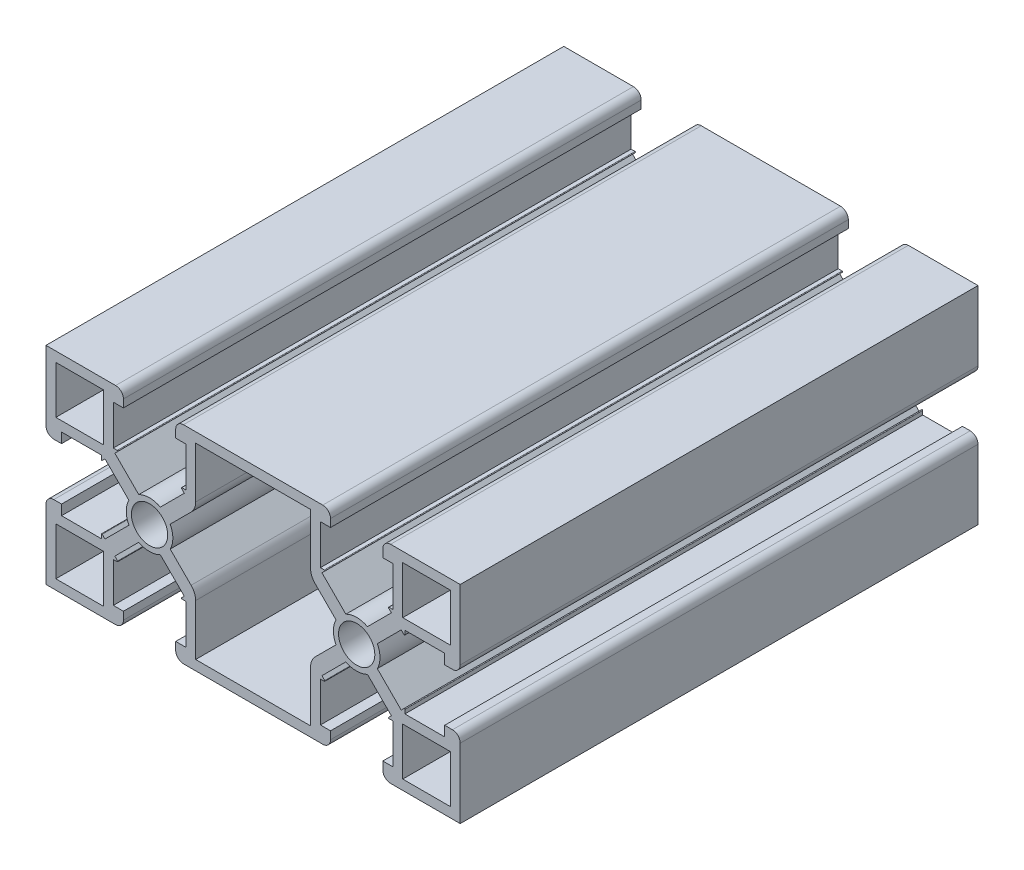
SolidWorks part; units mm, degrees
ref_plane "前视基准面" through (0, 0, 0) normal (0, 0, 1) x (1, 0, 0)
ref_plane "上视基准面" through (0, 0, 0) normal (0, 1, 0) x (1, 0, 0)
ref_plane "右视基准面" through (0, 0, 0) normal (1, 0, 0) x (0, 0, -1)
sketch "草图1" plane through (0, 0, 0) normal (0, 0, 1) x (1, 0, 0)
  line L0 (-40, 20) -> (-40, -20) construction
  line L1 (-27, 17) -> (-27, 9.3142)
  line L2 (-40, 20) -> (-40, 6.55)
  line L3 (-40, -20) -> (0, -20) construction
  line L4 (-40, 20) -> (-20, 0) construction
  line L5 (0, -20) -> (0, 20) construction
  line L6 (-28.9, 8.9) -> (-38.1, 8.9)
  line L7 (0, 0) -> (-40, 0) construction
  line L8 (-28.9, 8.9) -> (-28.9, 18.1)
  line L9 (-28.9, 18.1) -> (-38.1, 18.1)
  line L10 (-38.1, 8.9) -> (-38.1, 18.1)
  line L11 (-28.9, 8.9) -> (-38.1, 18.1) construction
  line L12 (-28.9, 18.1) -> (-38.1, 8.9) construction
  line L13 (-40, 20) -> (0, 20) construction
  line L14 (-38.5, 5.05) -> (-37, 5.05)
  line L15 (-25.05, 17) -> (-27, 17)
  line L16 (-25.05, 18.5) -> (-25.05, 17)
  line L17 (-40, 20) -> (-26.55, 20)
  line L18 (-26.7071, 8.6071) -> (-22.0869, 3.9869)
  line L19 (-37, 5.05) -> (-37, 7)
  line L20 (-37, 7) -> (-29.3142, 7)
  line L21 (-28.6071, 6.7071) -> (-23.9869, 2.0869)
  line L22 (-29.3142, 7) -> (-29.3142, 6.2414)
  line L23 (-29.1435, 6.1707) -> (-28.6071, 6.7071)
  line L24 (-29.3142, 7) -> (-28.9, 7) construction
  line L25 (-28.9, 7) -> (-28.6071, 6.7071) construction
  line L26 (-37, 7) -> (-37, 8.9) construction
  line L27 (-38.1, 8.9) -> (-40, 8.9) construction
  line L28 (-26.1707, 9.1435) -> (-26.7071, 8.6071)
  line L29 (-27, 9.3142) -> (-26.2414, 9.3142)
  line L30 (-20, 0) -> (-20, 20) construction
  line L31 (-13.2929, 8.6071) -> (-17.9131, 3.9869)
  line L32 (-13, 9.3142) -> (-13.7586, 9.3142)
  line L33 (-13.8293, 9.1435) -> (-13.2929, 8.6071)
  line L34 (-14.95, 18.5) -> (-14.95, 17)
  line L35 (-14.95, 17) -> (-13, 17)
  line L36 (-13, 17) -> (-13, 9.3142)
  line L37 (13.45, 20) -> (-13.45, 20)
  line L38 (13.45, -20) -> (-13.45, -20)
  line L39 (-11.9787, 6.1213) -> (-16.0131, 2.0869)
  line L40 (-11.1, 18.1) -> (-11.1, 8.2426)
  line L41 (-28.6071, 6.7071) -> (-26.7071, 8.6071) construction
  line L42 (-14.95, -18.5) -> (-14.95, -17)
  line L43 (-14.95, -17) -> (-13, -17)
  line L44 (-13, -17) -> (-13, -9.3142)
  line L45 (-13.8293, -9.1435) -> (-13.2929, -8.6071)
  line L46 (-13, -9.3142) -> (-13.7586, -9.3142)
  line L47 (-11.1, -18.1) -> (-11.1, -8.2426)
  line L48 (-11.9787, -6.1213) -> (-16.0131, -2.0869)
  line L49 (-13.2929, -8.6071) -> (-17.9131, -3.9869)
  line L50 (-26.7071, -8.6071) -> (-22.0869, -3.9869)
  line L51 (-28.6071, -6.7071) -> (-23.9869, -2.0869)
  line L52 (-29.3142, -7) -> (-29.3142, -6.2414)
  line L53 (-29.1435, -6.1707) -> (-28.6071, -6.7071)
  line L54 (-26.1707, -9.1435) -> (-26.7071, -8.6071)
  line L55 (-27, -9.3142) -> (-26.2414, -9.3142)
  line L56 (-27, -17) -> (-27, -9.3142)
  line L57 (-37, -7) -> (-29.3142, -7)
  line L58 (-37, -5.05) -> (-37, -7)
  line L59 (-38.5, -5.05) -> (-37, -5.05)
  line L60 (-40, -20) -> (-40, -6.55)
  line L61 (-38.1, -8.9) -> (-38.1, -18.1)
  line L62 (-28.9, -8.9) -> (-38.1, -8.9)
  line L63 (-28.9, -8.9) -> (-28.9, -18.1)
  line L64 (-28.9, -18.1) -> (-38.1, -18.1)
  line L65 (-25.05, -17) -> (-27, -17)
  line L66 (-25.05, -18.5) -> (-25.05, -17)
  line L67 (-40, -20) -> (-26.55, -20)
  line L68 (-11.1, 18.1) -> (11.1, 18.1)
  line L69 (-11.1, -18.1) -> (11.1, -18.1)
  line L70 (14.95, -18.5) -> (14.95, -17)
  line L71 (14.95, -17) -> (13, -17)
  line L72 (25.05, -17) -> (27, -17)
  line L73 (25.05, -18.5) -> (25.05, -17)
  line L74 (40, -20) -> (26.55, -20)
  line L75 (28.9, -18.1) -> (38.1, -18.1)
  line L76 (38.1, -8.9) -> (38.1, -18.1)
  line L77 (40, 20) -> (40, -20) construction
  line L78 (40, -20) -> (40, -6.55)
  line L79 (38.5, -5.05) -> (37, -5.05)
  line L80 (37, -5.05) -> (37, -7)
  line L81 (27, -9.3142) -> (26.2414, -9.3142)
  line L82 (26.1707, -9.1435) -> (26.7071, -8.6071)
  line L83 (27, -17) -> (27, -9.3142)
  line L84 (28.9, -8.9) -> (28.9, -18.1)
  line L85 (28.9, -8.9) -> (38.1, -8.9)
  line L86 (37, -7) -> (29.3142, -7)
  line L87 (29.3142, -7) -> (29.3142, -6.2414)
  line L88 (29.1435, -6.1707) -> (28.6071, -6.7071)
  line L89 (13.8293, -9.1435) -> (13.2929, -8.6071)
  line L90 (13, -9.3142) -> (13.7586, -9.3142)
  line L91 (13, -17) -> (13, -9.3142)
  line L92 (11.1, -18.1) -> (11.1, -8.2426)
  line L93 (13.2929, -8.6071) -> (17.9131, -3.9869)
  line L94 (28.6071, -6.7071) -> (23.9869, -2.0869)
  line L95 (26.7071, -8.6071) -> (22.0869, -3.9869)
  line L96 (11.9787, -6.1213) -> (16.0131, -2.0869)
  line L97 (11.9787, 6.1213) -> (16.0131, 2.0869)
  line L98 (13.2929, 8.6071) -> (17.9131, 3.9869)
  line L99 (13.8293, 9.1435) -> (13.2929, 8.6071)
  line L100 (13, 9.3142) -> (13.7586, 9.3142)
  line L101 (13, 17) -> (13, 9.3142)
  line L102 (14.95, 17) -> (13, 17)
  line L103 (11.1, 18.1) -> (11.1, 8.2426)
  line L104 (14.95, 18.5) -> (14.95, 17)
  line L105 (37, 5.05) -> (37, 7)
  line L106 (29.3142, 7) -> (29.3142, 6.2414)
  line L107 (29.1435, 6.1707) -> (28.6071, 6.7071)
  line L108 (28.6071, 6.7071) -> (23.9869, 2.0869)
  line L109 (26.7071, 8.6071) -> (22.0869, 3.9869)
  line L110 (26.1707, 9.1435) -> (26.7071, 8.6071)
  line L111 (27, 9.3142) -> (26.2414, 9.3142)
  line L112 (38.5, 5.05) -> (37, 5.05)
  line L113 (37, 7) -> (29.3142, 7)
  line L114 (28.9, 8.9) -> (38.1, 8.9)
  line L115 (25.05, 18.5) -> (25.05, 17)
  line L116 (25.05, 17) -> (27, 17)
  line L117 (27, 17) -> (27, 9.3142)
  line L118 (28.9, 8.9) -> (28.9, 18.1)
  line L119 (38.1, 8.9) -> (38.1, 18.1)
  line L120 (28.9, 18.1) -> (38.1, 18.1)
  line L121 (40, 20) -> (40, 6.55)
  line L122 (40, 20) -> (26.55, 20)
  arc A0 (-23.9869, 2.0869) -> (-23.9869, -2.0869) centre (-20, 0) ccw
  arc A1 (-40, 6.55) -> (-38.5, 5.05) centre (-38.5, 6.55) ccw
  circle A2 centre (-20, 0) radius 3.5
  arc A3 (-26.55, 20) -> (-25.05, 18.5) centre (-26.55, 18.5) cw
  arc A4 (-29.3142, 6.2414) -> (-29.1435, 6.1707) centre (-29.2142, 6.2414) ccw
  arc A5 (-26.2414, 9.3142) -> (-26.1707, 9.1435) centre (-26.2414, 9.2142) cw
  arc A6 (-13.45, 20) -> (-14.95, 18.5) centre (-13.45, 18.5) ccw
  arc A7 (-13.7586, 9.3142) -> (-13.8293, 9.1435) centre (-13.7586, 9.2142) ccw
  arc A8 (-11.9787, 6.1213) -> (-11.1, 8.2426) centre (-14.1, 8.2426) ccw
  arc A9 (-13.45, -20) -> (-14.95, -18.5) centre (-13.45, -18.5) cw
  arc A10 (-13.7586, -9.3142) -> (-13.8293, -9.1435) centre (-13.7586, -9.2142) cw
  arc A11 (-11.9787, -6.1213) -> (-11.1, -8.2426) centre (-14.1, -8.2426) cw
  arc A12 (-29.3142, -6.2414) -> (-29.1435, -6.1707) centre (-29.2142, -6.2414) cw
  arc A13 (-26.2414, -9.3142) -> (-26.1707, -9.1435) centre (-26.2414, -9.2142) ccw
  arc A14 (-40, -6.55) -> (-38.5, -5.05) centre (-38.5, -6.55) cw
  arc A15 (-26.55, -20) -> (-25.05, -18.5) centre (-26.55, -18.5) ccw
  arc A16 (-17.9131, 3.9869) -> (-22.0869, 3.9869) centre (-20, 0) ccw
  arc A17 (-16.0131, -2.0869) -> (-16.0131, 2.0869) centre (-20, 0) ccw
  arc A18 (-22.0869, -3.9869) -> (-17.9131, -3.9869) centre (-20, 0) ccw
  arc A19 (13.45, -20) -> (14.95, -18.5) centre (13.45, -18.5) ccw
  arc A20 (26.55, -20) -> (25.05, -18.5) centre (26.55, -18.5) cw
  arc A21 (40, -6.55) -> (38.5, -5.05) centre (38.5, -6.55) ccw
  arc A22 (26.2414, -9.3142) -> (26.1707, -9.1435) centre (26.2414, -9.2142) cw
  arc A23 (29.3142, -6.2414) -> (29.1435, -6.1707) centre (29.2142, -6.2414) ccw
  arc A24 (13.7586, -9.3142) -> (13.8293, -9.1435) centre (13.7586, -9.2142) ccw
  arc A25 (11.9787, -6.1213) -> (11.1, -8.2426) centre (14.1, -8.2426) ccw
  arc A26 (22.0869, -3.9869) -> (17.9131, -3.9869) centre (20, 0) cw
  circle A27 centre (20, 0) radius 3.5
  arc A28 (23.9869, 2.0869) -> (23.9869, -2.0869) centre (20, 0) cw
  arc A29 (16.0131, -2.0869) -> (16.0131, 2.0869) centre (20, 0) cw
  arc A30 (17.9131, 3.9869) -> (22.0869, 3.9869) centre (20, 0) cw
  arc A31 (13.7586, 9.3142) -> (13.8293, 9.1435) centre (13.7586, 9.2142) cw
  arc A32 (11.9787, 6.1213) -> (11.1, 8.2426) centre (14.1, 8.2426) cw
  arc A33 (13.45, 20) -> (14.95, 18.5) centre (13.45, 18.5) cw
  arc A34 (29.3142, 6.2414) -> (29.1435, 6.1707) centre (29.2142, 6.2414) cw
  arc A35 (26.2414, 9.3142) -> (26.1707, 9.1435) centre (26.2414, 9.2142) ccw
  arc A36 (40, 6.55) -> (38.5, 5.05) centre (38.5, 6.55) cw
  arc A37 (26.55, 20) -> (25.05, 18.5) centre (26.55, 18.5) ccw
  point P0 (0, 0)
  point P10 (-33.5, 13.5)
  point P26 (-40, 5.05)
  point P39 (-29.3142, 6)
  point P109 (0, -18.1)
  point P164 (0, 18.1)
  dimension "D" = 7
  dimension "D4" = 9
  dimension "D9" = 0.1
  dimension "D12" = 3
  dimension "D6" = 1.5
  dimension "L1" = 80
  dimension "L2" = 40
  dimension "G2" = 1.9
  dimension "K1" = 14
  dimension "G1" = 3
  dimension "D8" = 1
  dimension "K2" = 10.1
extrude "凸台-拉伸3" add sketch "草图1" against normal blind 100
